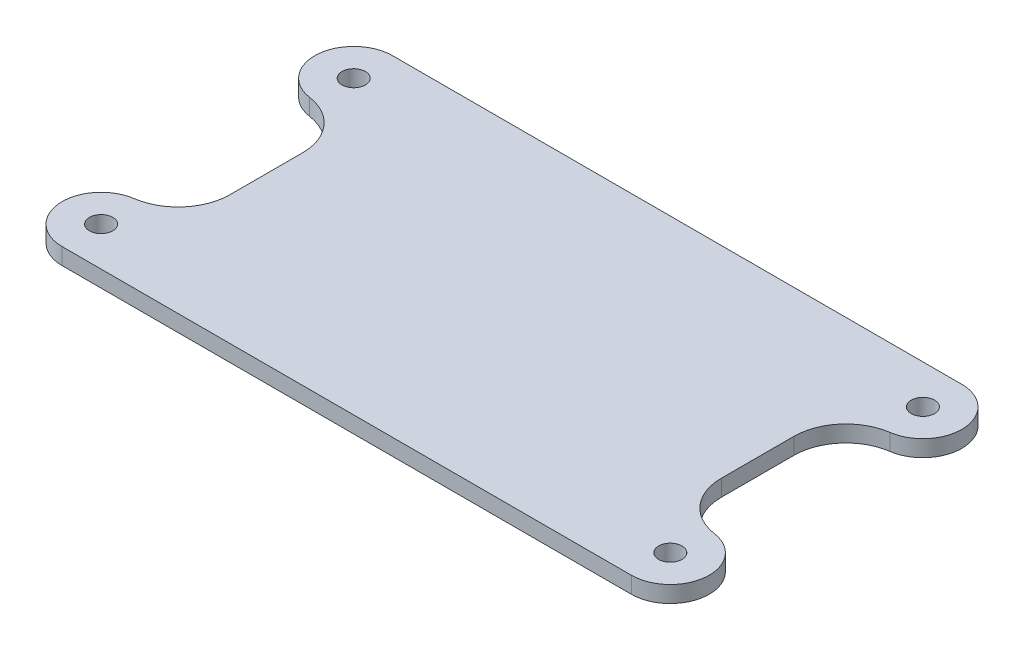
SolidWorks part; units mm, degrees
ref_plane "Front Plane" through (0, 0, 0) normal (0, 0, 1) x (1, 0, 0)
ref_plane "Top Plane" through (0, 0, 0) normal (0, 1, 0) x (1, 0, 0)
ref_plane "Right Plane" through (0, 0, 0) normal (1, 0, 0) x (0, 0, -1)
sketch "Sketch1" plane through (0, 0, 0) normal (0, 1, 0) x (1, 0, 0)
  line L15 (-47.25, 6.9765) -> (-47.25, -6.9765)
  line L17 (-54.75, -31.797) -> (54.75, -31.797)
  line L19 (47.25, -6.9765) -> (47.25, 6.9765)
  line L21 (54.75, 31.797) -> (-54.75, 31.797)
  line L23 (-47.25, 6.9765) -> (-47.25, -6.9765)
  line L25 (-54.75, -31.797) -> (54.75, -31.797)
  line L27 (47.25, -6.9765) -> (47.25, 6.9765)
  line L29 (54.75, 31.797) -> (-54.75, 31.797)
  circle A0 centre (54.75, 24.297) radius 2.2479 construction
  circle A1 centre (54.75, -24.297) radius 2.2479 construction
  circle A2 centre (-54.75, -24.297) radius 2.2479 construction
  circle A3 centre (-54.75, 24.297) radius 2.2479 construction
  circle A4 centre (54.75, 24.297) radius 2.2479
  circle A5 centre (54.75, -24.297) radius 2.2479
  circle A6 centre (-54.75, -24.297) radius 2.2479
  circle A7 centre (-54.75, 24.297) radius 2.2479
  arc A8 (-54.75, 31.797) -> (-62.25, 24.297) centre (-54.75, 24.297) ccw
  arc A9 (-62.25, 24.297) -> (-55.8214, 16.8739) centre (-54.75, 24.297) ccw
  arc A10 (-55.8214, -16.8739) -> (-62.25, -24.297) centre (-54.75, -24.297) ccw
  arc A11 (-62.25, -24.297) -> (-54.75, -31.797) centre (-54.75, -24.297) ccw
  arc A12 (54.75, -31.797) -> (62.25, -24.297) centre (54.75, -24.297) ccw
  arc A13 (62.25, -24.297) -> (55.8214, -16.8739) centre (54.75, -24.297) ccw
  arc A14 (55.8214, 16.8739) -> (62.25, 24.297) centre (54.75, 24.297) ccw
  arc A15 (62.25, 24.297) -> (54.75, 31.797) centre (54.75, 24.297) ccw
  arc A16 (-54.75, 31.797) -> (-62.25, 24.297) centre (-54.75, 24.297) ccw
  arc A17 (-62.25, 24.297) -> (-55.8214, 16.8739) centre (-54.75, 24.297) ccw
  arc A18 (-55.8214, -16.8739) -> (-62.25, -24.297) centre (-54.75, -24.297) ccw
  arc A19 (-62.25, -24.297) -> (-54.75, -31.797) centre (-54.75, -24.297) ccw
  arc A20 (54.75, -31.797) -> (62.25, -24.297) centre (54.75, -24.297) ccw
  arc A21 (62.25, -24.297) -> (55.8214, -16.8739) centre (54.75, -24.297) ccw
  arc A22 (55.8214, 16.8739) -> (62.25, 24.297) centre (54.75, 24.297) ccw
  arc A23 (62.25, 24.297) -> (54.75, 31.797) centre (54.75, 24.297) ccw
  arc A80 (-47.25, 6.9765) -> (-55.8214, 16.8739) centre (-57.25, 6.9765) ccw
  arc A81 (-47.25, 6.9765) -> (-55.8214, 16.8739) centre (-57.25, 6.9765) ccw
  arc A82 (-55.8214, -16.8739) -> (-47.25, -6.9765) centre (-57.25, -6.9765) ccw
  arc A83 (-55.8214, -16.8739) -> (-47.25, -6.9765) centre (-57.25, -6.9765) ccw
  arc A84 (47.25, -6.9765) -> (55.8214, -16.8739) centre (57.25, -6.9765) ccw
  arc A85 (47.25, -6.9765) -> (55.8214, -16.8739) centre (57.25, -6.9765) ccw
  arc A86 (55.8214, 16.8739) -> (47.25, 6.9765) centre (57.25, 6.9765) ccw
  arc A87 (55.8214, 16.8739) -> (47.25, 6.9765) centre (57.25, 6.9765) ccw
  point P0 (0, 0)
  dimension "D1" = 0
extrude "Boss-Extrude1" add sketch "Sketch1" along normal mid plane 3.175
